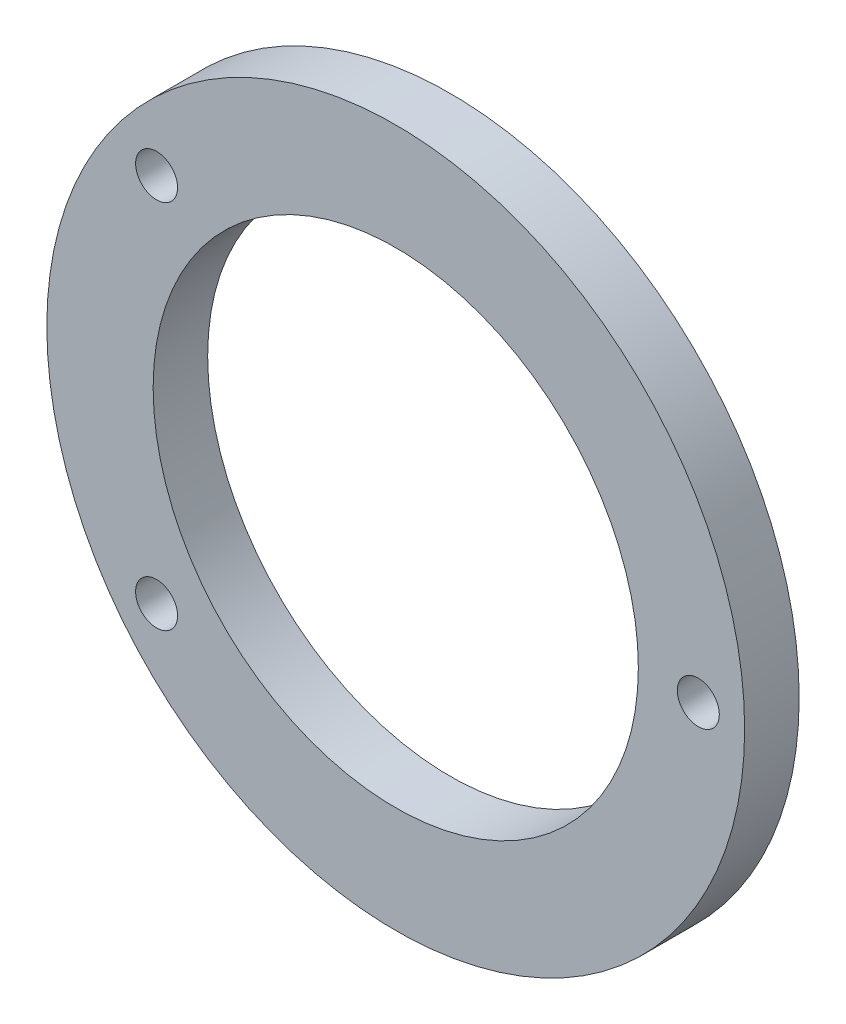
SolidWorks part; units mm, degrees
ref_plane "Plan de face" through (0, 0, 0) normal (0, 0, 1) x (1, 0, 0)
ref_plane "Plan de dessus" through (0, 0, 0) normal (0, 1, 0) x (1, 0, 0)
ref_plane "Plan de droite" through (0, 0, 0) normal (1, 0, 0) x (0, 0, -1)
sketch "Esquisse3" plane through (0, 0, 0) normal (0, 0, 1) x (1, 0, 0)
  line L0 (0, 0) -> (-21.9331, 17) construction
  line L2 (27.75, 0) -> (0, 0) construction
  line L3 (0, 0) -> (-21.9331, -17) construction
  circle A0 centre (0, 0) radius 22.25
  circle A1 centre (0, 0) radius 32
  circle A8 centre (27.75, 0) radius 1.925
  circle A9 centre (-21.9331, 17) radius 1.925
  circle A10 centre (-21.9331, -17) radius 1.925
  circle A11 centre (0, 0) radius 27.75 construction
  dimension "D3" = 55.5
  dimension "D4" = 44.5
  dimension "D5" = 64
  dimension "D6" = 3.85
  dimension "D1" = 142.221
  dimension "D2" = 142.221
extrude "Boss.-Extru.1" add sketch "Esquisse3" along normal blind 5
